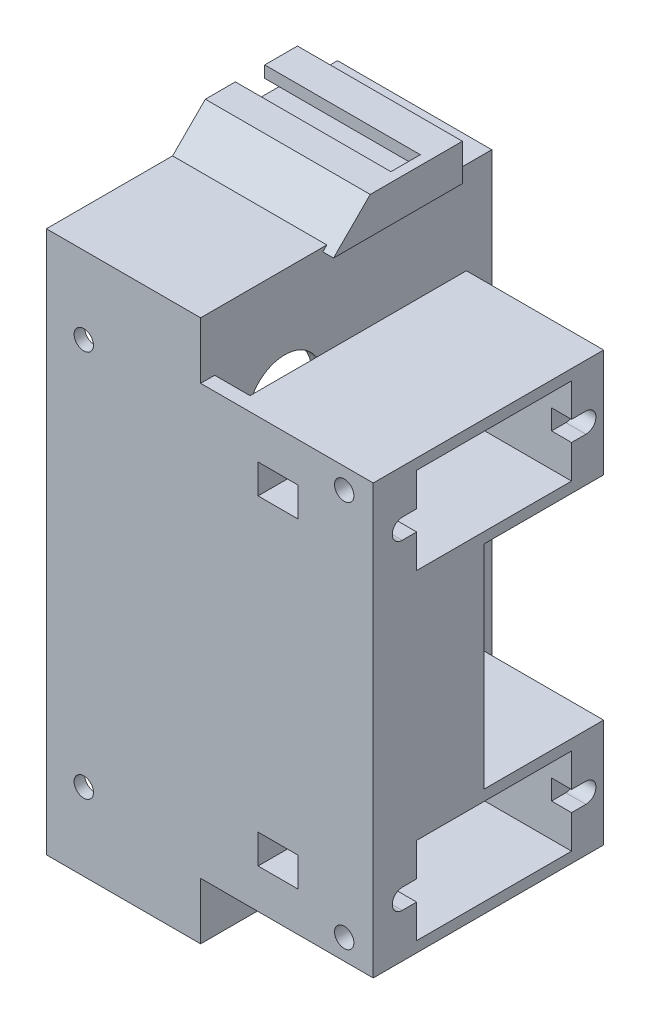
SolidWorks part; units mm, degrees
material "ABS"
ref_plane "Front Plane" through (0, 0, 0) normal (0, 0, 1) x (1, 0, 0)
ref_plane "Top Plane" through (0, 0, 0) normal (0, 1, 0) x (1, 0, 0)
ref_plane "Right Plane" through (0, 0, 0) normal (1, 0, 0) x (0, 0, -1)
sketch "Sketch1" plane through (0, 0, 0) normal (1, 0, 0) x (0, 0, -1)
  line L1 (-12.6, -40.6) -> (31, -40.6)
  line L2 (-12.6, -40.6) -> (-12.6, 40.6)
  line L3 (-12.6, 40.6) -> (31, 40.6)
  line L4 (31, -40.6) -> (31, 40.6)
extrude "Boss-Extrude1" add sketch "Sketch1" along normal mid plane 23.1 from offset 88.55
sketch "Sketch2" plane through (0, 0, 0) normal (0, 0, 1) x (1, 0, 0)
  line L1 (-71.7, -16.5) -> (-51.15, -16.5)
  line L2 (-71.7, -16.5) -> (-71.7, 16.5)
  line L3 (-71.7, 16.5) -> (-51.15, 16.5)
  line L4 (-51.15, -16.5) -> (-51.15, 16.5)
extrude "Boss-Extrude2" add sketch "Sketch2" along normal mid plane 14.9 from offset 3.45
sketch "Sketch3" plane through (0, 0, 0) normal (0, 0, 1) x (1, 0, 0)
  line L0 (-71.7, 16.5) -> (-71.7, -16.5) construction
  line L1 (-78, -6.5) -> (-71.7, -6.5)
  line L2 (-78, -6.5) -> (-78, 6.5)
  line L3 (-78, 6.5) -> (-71.7, 6.5)
  line L4 (-71.7, -6.5) -> (-71.7, 6.5)
extrude "Boss-Extrude3" add sketch "Sketch3" along normal mid plane 12.9 from offset 4.45
sketch "Sketch4" plane through (0, 0, 0) normal (0, 0, 1) x (1, 0, 0)
  line L1 (-78, -32.1) -> (-51.15, -32.1)
  line L2 (-78, -32.1) -> (-78, 32.1)
  line L3 (-78, 32.1) -> (-51.15, 32.1)
  line L4 (-51.15, -32.1) -> (-51.15, 32.1)
extrude "Boss-Extrude4" add sketch "Sketch4" along normal mid plane 2.1 from offset 11.55
sketch "Sketch5" plane through (0, 0, 0) normal (1, 0, 0) x (0, 0, -1)
  line L1 (-10.9, 15.9) -> (21.9, 15.9)
  line L2 (-10.9, 15.9) -> (-10.9, 32.1)
  line L3 (-10.9, 32.1) -> (21.9, 32.1)
  line L4 (21.9, 15.9) -> (21.9, 32.1)
extrude "Boss-Extrude5" add sketch "Sketch5" along normal mid plane 20.55 from offset 61.425
sketch "Sketch6" plane through (0, 0, 0) normal (1, 0, 0) x (0, 0, -1)
  line L0 (25, 40) -> (25, 45.5)
  line L1 (25, 45.5) -> (11.2, 45.5)
  line L2 (11.2, 45.5) -> (5.7, 40)
  line L3 (5.7, 40) -> (25, 40)
extrude "Boss-Extrude6" add sketch "Sketch6" along normal mid plane 24.7 from offset 87.75
sketch "Sketch7" plane through (0, 0, 0) normal (1, 0, 0) x (0, 0, -1)
  line L0 (-12.6, -32.1) -> (-10.5, -32.1) construction
  line L1 (-10.9, -32.1) -> (21.9, -32.1)
  line L2 (-10.9, -32.1) -> (-10.9, -15.9)
  line L3 (-10.9, -15.9) -> (21.9, -15.9)
  line L4 (21.9, -32.1) -> (21.9, -15.9)
extrude "Boss-Extrude7" add sketch "Sketch7" along normal mid plane 20.55 from offset 61.425
sketch "Sketch8" plane through (0, 0, 0) normal (1, 0, 0) x (0, 0, -1)
  line L0 (25, -40) -> (25, -45.5)
  line L1 (25, -45.5) -> (11.2, -45.5)
  line L2 (11.2, -45.5) -> (5.7, -40)
  line L3 (5.7, -40) -> (25, -40)
extrude "Boss-Extrude8" add sketch "Sketch8" along normal mid plane 24.7 from offset 87.75
sketch "Sketch9" plane through (0, 0, 0) normal (1, 0, 0) x (0, 0, -1)
  line L1 (-11, -39) -> (32, -39)
  line L2 (-11, -39) -> (-11, 39)
  line L3 (-11, 39) -> (32, 39)
  line L4 (32, -39) -> (32, 39)
extrude "Cut-Extrude1" cut sketch "Sketch9" against normal mid plane 21.6 from offset 89.3
sketch "Sketch10" plane through (0, 0, 0) normal (0, 0, 1) x (1, 0, 0)
  circle A0 centre (-94.5, -29) radius 1.45
  circle A1 centre (-94.5, 29) radius 1.45
  circle A2 centre (-55.5, -29) radius 1.45
  circle A3 centre (-55.5, 29) radius 1.45
extrude "Cut-Extrude2" cut sketch "Sketch10" against normal mid plane 2.2 from offset 11.5
sketch "Sketch11" plane through (0, 0, 0) normal (1, 0, 0) x (0, 0, -1)
  line L0 (20.1, 45.5) -> (15.7, 45.5)
  line L1 (25, 45.5) -> (11.2, 45.5) construction
  line L2 (15.7, 45.5) -> (15.7, 43.75)
  line L3 (15.7, 43.75) -> (13.55, 41.6)
  line L4 (13.55, 41.6) -> (22.25, 41.6)
  line L5 (22.25, 41.6) -> (20.1, 43.75)
  line L6 (20.1, 43.75) -> (20.1, 45.5)
extrude "Cut-Extrude3" cut sketch "Sketch11" against normal mid plane 23.3 from offset 88.45
sketch "Sketch12" plane through (0, 0, 0) normal (1, 0, 0) x (0, 0, -1)
  line L1 (-6.1, 17.5) -> (17.1, 17.5)
  line L2 (-6.1, 17.5) -> (-6.1, 30.5)
  line L3 (-6.1, 30.5) -> (17.1, 30.5)
  line L4 (17.1, 17.5) -> (17.1, 30.5)
extrude "Cut-Extrude4" cut sketch "Sketch12" against normal mid plane 17.25 from offset 59.775
sketch "Sketch13" plane through (0, 0, 0) normal (1, 0, 0) x (0, 0, -1)
  circle A0 centre (19.25, 24) radius 1.5
extrude "Cut-Extrude5" cut sketch "Sketch13" against normal mid plane 3 from offset 52.65
sketch "Sketch14" plane through (0, 0, 0) normal (1, 0, 0) x (0, 0, -1)
  line L0 (17.1, 17.5) -> (17.1, 30.5) construction
  line L1 (17.1, 22.5) -> (19.25, 22.5)
  line L2 (17.1, 22.5) -> (17.1, 25.5)
  line L3 (17.1, 25.5) -> (19.25, 25.5)
  line L4 (19.25, 22.5) -> (19.25, 25.5)
  circle A0 centre (19.25, 24) radius 1.5 construction
extrude "Cut-Extrude6" cut sketch "Sketch14" against normal mid plane 3 from offset 52.65
sketch "Sketch15" plane through (0, 0, 0) normal (1, 0, 0) x (0, 0, -1)
  circle A0 centre (-8.25, 24) radius 1.5
extrude "Cut-Extrude7" cut sketch "Sketch15" against normal mid plane 3 from offset 52.65
sketch "Sketch16" plane through (0, 0, 0) normal (1, 0, 0) x (0, 0, -1)
  line L0 (-6.1, 30.5) -> (-6.1, 17.5) construction
  line L1 (-8.25, 22.5) -> (-6.1, 22.5)
  line L2 (-8.25, 22.5) -> (-8.25, 25.5)
  line L3 (-8.25, 25.5) -> (-6.1, 25.5)
  line L4 (-6.1, 22.5) -> (-6.1, 25.5)
  circle A0 centre (-8.25, 24) radius 1.5 construction
extrude "Cut-Extrude8" cut sketch "Sketch16" against normal mid plane 3 from offset 52.65
sketch "Sketch17" plane through (0, 0, 0) normal (1, 0, 0) x (0, 0, -1)
  circle A0 centre (0, 24) radius 3.15
extrude "Cut-Extrude9" cut sketch "Sketch17" against normal mid plane 2.6 from offset 70.4
sketch "Sketch18" plane through (0, 0, 0) normal (0, 0, 1) x (1, 0, 0)
  line L1 (-68.4, 21.8) -> (-62.4, 21.8)
  line L2 (-68.4, 21.8) -> (-68.4, 26.2)
  line L3 (-68.4, 26.2) -> (-62.4, 26.2)
  line L4 (-62.4, 21.8) -> (-62.4, 26.2)
extrude "Cut-Extrude10" cut sketch "Sketch18" against normal mid plane 4.8 from offset 8.5
sketch "Sketch19" plane through (0, 0, 0) normal (0, 0, 1) x (1, 0, 0)
  line L1 (-68.4, 21.8) -> (-62.4, 21.8)
  line L2 (-68.4, 21.8) -> (-68.4, 26.2)
  line L3 (-68.4, 26.2) -> (-62.4, 26.2)
  line L4 (-62.4, 21.8) -> (-62.4, 26.2)
extrude "Cut-Extrude11" cut sketch "Sketch19" against normal mid plane 2.2 from offset 11.5
sketch "Sketch20" plane through (0, 0, 0) normal (1, 0, 0) x (0, 0, -1)
  circle A0 centre (0, 24) radius 5.5
extrude "Cut-Extrude12" cut sketch "Sketch20" against normal mid plane 1.5 from offset 77.75
sketch "Sketch21" plane through (0, 0, 0) normal (1, 0, 0) x (0, 0, -1)
  line L0 (20.1, -45.5) -> (15.7, -45.5)
  line L1 (11.2, -45.5) -> (25, -45.5) construction
  line L2 (15.7, -45.5) -> (15.7, -43.75)
  line L3 (15.7, -43.75) -> (13.55, -41.6)
  line L4 (13.55, -41.6) -> (22.25, -41.6)
  line L5 (22.25, -41.6) -> (20.1, -43.75)
  line L6 (20.1, -43.75) -> (20.1, -45.5)
extrude "Cut-Extrude13" cut sketch "Sketch21" against normal mid plane 23.3 from offset 88.45
sketch "Sketch22" plane through (0, 0, 0) normal (1, 0, 0) x (0, 0, -1)
  line L1 (-6.1, -30.5) -> (17.1, -30.5)
  line L2 (-6.1, -30.5) -> (-6.1, -17.5)
  line L3 (-6.1, -17.5) -> (17.1, -17.5)
  line L4 (17.1, -30.5) -> (17.1, -17.5)
extrude "Cut-Extrude14" cut sketch "Sketch22" against normal mid plane 17.25 from offset 59.775
sketch "Sketch23" plane through (0, 0, 0) normal (1, 0, 0) x (0, 0, -1)
  circle A0 centre (19.25, -24) radius 1.5
extrude "Cut-Extrude15" cut sketch "Sketch23" against normal mid plane 3 from offset 52.65
sketch "Sketch24" plane through (0, 0, 0) normal (1, 0, 0) x (0, 0, -1)
  line L0 (17.1, -30.5) -> (17.1, -17.5) construction
  line L1 (17.1, -25.5) -> (19.25, -25.5)
  line L2 (17.1, -25.5) -> (17.1, -22.5)
  line L3 (17.1, -22.5) -> (19.25, -22.5)
  line L4 (19.25, -25.5) -> (19.25, -22.5)
  circle A0 centre (19.25, -24) radius 1.5 construction
extrude "Cut-Extrude16" cut sketch "Sketch24" against normal mid plane 3 from offset 52.65
sketch "Sketch25" plane through (0, 0, 0) normal (1, 0, 0) x (0, 0, -1)
  circle A0 centre (-8.25, -24) radius 1.5
extrude "Cut-Extrude17" cut sketch "Sketch25" against normal mid plane 3 from offset 52.65
sketch "Sketch26" plane through (0, 0, 0) normal (1, 0, 0) x (0, 0, -1)
  line L0 (-6.1, -17.5) -> (-6.1, -30.5) construction
  line L1 (-8.25, -25.5) -> (-6.1, -25.5)
  line L2 (-8.25, -25.5) -> (-8.25, -22.5)
  line L3 (-8.25, -22.5) -> (-6.1, -22.5)
  line L4 (-6.1, -25.5) -> (-6.1, -22.5)
  circle A0 centre (-8.25, -24) radius 1.5 construction
extrude "Cut-Extrude18" cut sketch "Sketch26" against normal mid plane 3 from offset 52.65
sketch "Sketch27" plane through (0, 0, 0) normal (1, 0, 0) x (0, 0, -1)
  circle A0 centre (0, -24) radius 3.15
extrude "Cut-Extrude19" cut sketch "Sketch27" against normal mid plane 2.6 from offset 70.4
sketch "Sketch28" plane through (0, 0, 0) normal (0, 0, 1) x (1, 0, 0)
  line L1 (-68.4, -26.2) -> (-62.4, -26.2)
  line L2 (-68.4, -26.2) -> (-68.4, -21.8)
  line L3 (-68.4, -21.8) -> (-62.4, -21.8)
  line L4 (-62.4, -26.2) -> (-62.4, -21.8)
extrude "Cut-Extrude20" cut sketch "Sketch28" against normal mid plane 4.8 from offset 8.5
sketch "Sketch29" plane through (0, 0, 0) normal (0, 0, 1) x (1, 0, 0)
  line L1 (-68.4, -26.2) -> (-62.4, -26.2)
  line L2 (-68.4, -26.2) -> (-68.4, -21.8)
  line L3 (-68.4, -21.8) -> (-62.4, -21.8)
  line L4 (-62.4, -26.2) -> (-62.4, -21.8)
extrude "Cut-Extrude21" cut sketch "Sketch29" against normal mid plane 2.2 from offset 11.5
sketch "Sketch30" plane through (0, 0, 0) normal (1, 0, 0) x (0, 0, -1)
  circle A0 centre (0, -24) radius 5.5
extrude "Cut-Extrude22" cut sketch "Sketch30" against normal mid plane 1.5 from offset 77.75
